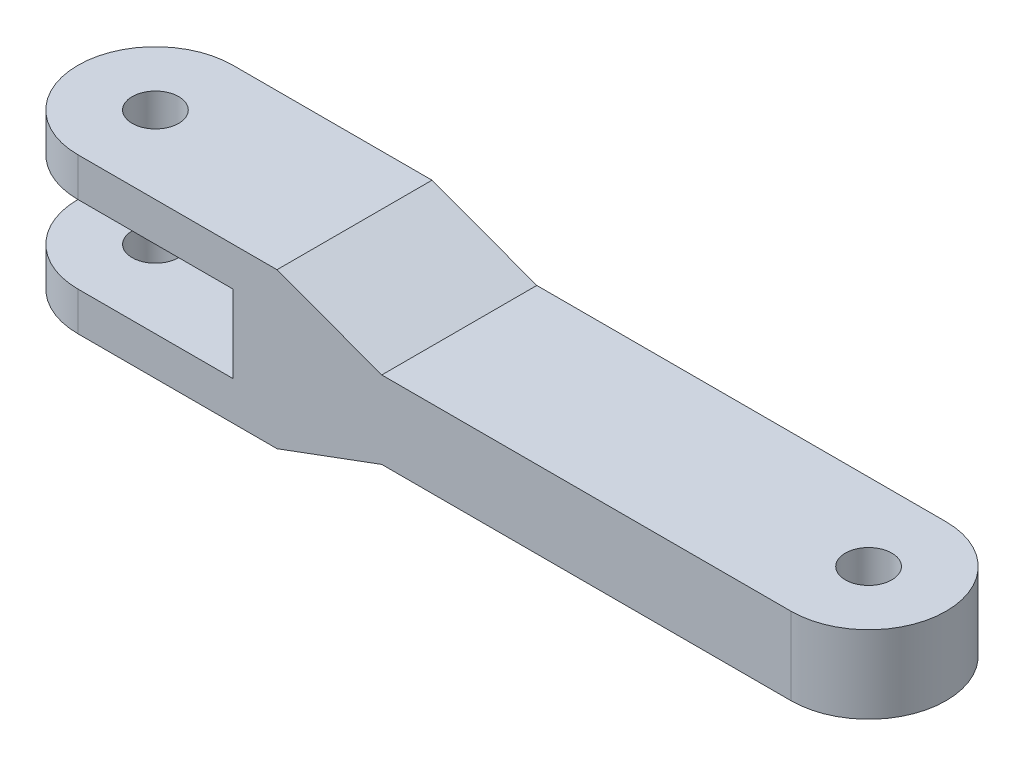
SolidWorks part; units mm, degrees
ref_plane "Alzado" through (0, 0, 0) normal (0, 0, 1) x (1, 0, 0)
ref_plane "Planta" through (0, 0, 0) normal (0, 1, 0) x (1, 0, 0)
ref_plane "Vista lateral" through (0, 0, 0) normal (1, 0, 0) x (0, 0, -1)
sketch "Croquis1" plane through (0, 0, 0) normal (0, 0, 1) x (1, 0, 0)
  line L1 (0, 0) -> (39.6, 0)
  line L2 (0, 0) -> (0, 2.5)
  line L3 (0, 10) -> (39.6, 10)
  line L5 (39.6, 2.5) -> (39.6, 0)
  line L7 (0, 7.5) -> (0, 10)
  line L9 (0, 7.5) -> (15, 7.5)
  line L12 (39.6, 7.5) -> (39.6, 10)
  line L13 (39.6, 7.5) -> (39.6, 2.5)
  line L14 (0, 2.5) -> (15, 2.5)
  line L15 (15, 7.5) -> (15, 2.5)
  dimension "D1" = 15
  dimension "D2" = 10
  dimension "D3" = 39.6
extrude "Saliente-Extruir1" add sketch "Croquis1" along normal blind 10
sketch "Croquis2" plane through (0, 10, 0) normal (0, 1, 0) x (1, 0, 0)
  line L1 (0, -10) -> (0, 0) construction
  line L3 (-4.0319, 0) -> (5, 0)
  line L4 (-4.0319, 0) -> (-4.0319, -10)
  line L5 (-4.0319, -10) -> (5, -10)
  circle A0 centre (5, -5) radius 1.5
  arc A2 (5, 0) -> (5, -10) centre (5, -5) ccw
  dimension "D1" = 3
  dimension "D2" = 5
extrude "Cortar-Extruir1" cut sketch "Croquis2" against normal blind 10
sketch "Croquis3" plane through (0, 10, 0) normal (0, 1, 0) x (1, 0, 0)
  line L0 (39.6, -5) -> (87.1029, -5) construction
  line L1 (39.6, -10) -> (39.6, 0) construction
  line L2 (39.6, 0) -> (5, 0) construction
  line L3 (24.6, 0) -> (39.6, 0)
  line L4 (24.6, 0) -> (24.6, -2.5)
  line L5 (24.6, -2.5) -> (39.6, -2.5)
  line L6 (39.6, 0) -> (39.6, -2.5)
  line L7 (39.6, -10) -> (39.6, -7.5)
  line L8 (24.6, -7.5) -> (39.6, -7.5)
  line L9 (24.6, -10) -> (24.6, -7.5)
  line L10 (24.6, -10) -> (39.6, -10)
  dimension "D1" = 15
  dimension "D2" = 2.5
extrude "Cortar-Extruir2" cut sketch "Croquis3" against normal blind 10
sketch "Croquis4" plane through (0, 0, 7.5) normal (0, 0, 1) x (1, 0, 0)
  line L0 (39.6, 0) -> (39.6, 10) construction
  line L1 (34.6, 10) -> (103.0041, 10)
  line L2 (103.0041, 10) -> (103.0041, 0)
  line L3 (103.0041, 0) -> (34.6, 0)
  circle A0 centre (34.6, 5) radius 1.5
  arc A1 (34.6, 0) -> (34.6, 10) centre (34.6, 5) ccw
  dimension "D2" = 10
  dimension "D3" = 3
  dimension "D1" = 5
extrude "Cortar-Extruir3" cut sketch "Croquis4" against normal blind 10
sketch "Croquis8" plane through (0, 0, 7.5) normal (0, 0, 1) x (1, 0, 0)
  line L3 (24.6, 0) -> (34.6, 0)
  line L4 (34.6, 10) -> (24.6, 10)
  line L5 (24.6, 10) -> (24.6, 0)
  line L6 (24.6, 0) -> (34.6, 0)
  line L7 (34.6, 10) -> (24.6, 10)
  line L8 (24.6, 10) -> (24.6, 0)
  arc A1 (34.6, 0) -> (34.6, 10) centre (34.6, 5) ccw
  arc A2 (34.6, 0) -> (34.6, 10) centre (34.6, 5) ccw
  dimension "D1" = 0
extrude "Cortar-Extruir5" cut sketch "Croquis8" against normal blind 10
ref_plane "Plano1" through (0, 5, 0) normal (0, -1, 0) x (-1, 0, 0)
sketch "Croquis9" plane through (0, 5, 0) normal (0, -1, 0) x (-1, 0, 0)
  line L0 (-24.6, 0) -> (-24.6, -10) construction
  line L1 (-24.6, -10) -> (-95, -10)
  line L2 (-24.6, -10) -> (-24.6, 0)
  line L3 (-24.6, 0) -> (-95, 0)
  circle A0 centre (-95, -5) radius 1.5
  arc A1 (-95, 0) -> (-95, -10) centre (-95, -5) ccw
  dimension "D2" = 3
extrude "Saliente-Extruir2" add sketch "Croquis9" along normal mid plane 5
sketch "Croquis11" plane through (0, 2.5, 0) normal (0, -1, 0) x (1, 0, 0)
  line L0 (51, 10) -> (51, 16.0198)
  line L1 (51, 16.0198) -> (124.4517, 16.0198)
  line L2 (124.4517, 16.0198) -> (123.0247, -12.8378)
  line L3 (123.0247, -12.8378) -> (54.8387, -9.466)
  line L4 (54.8387, -9.466) -> (51, 0)
  circle A0 centre (51, 5) radius 1.5
  arc A1 (51, 0) -> (51, 10) centre (51, 5) ccw
  dimension "D1" = 3
  dimension "D2" = 51
extrude "Cortar-Extruir8" cut sketch "Croquis11" against normal blind 10
sketch "Croquis12" plane through (0, 0, 10) normal (0, 0, 1) x (1, 0, 0)
  line L0 (24.6, 7.5) -> (17.842, 10)
  line L1 (24.6, 10) -> (5, 10) construction
  line L2 (17.842, 10) -> (24.6, 10)
  line L3 (24.6, 10) -> (24.6, 7.5)
  line L4 (56, 5) -> (33.7023, 5) construction
  line L5 (56, 2.5) -> (56, 7.5) construction
  line L6 (-5.5, 5) -> (5.5, 5) construction
  line L7 (24.6, 2.5) -> (17.842, 0)
  line L8 (24.6, 0) -> (24.6, 2.5)
  line L9 (17.842, 0) -> (24.6, 0)
extrude "Cortar-Extruir9" cut sketch "Croquis12" against normal through all
